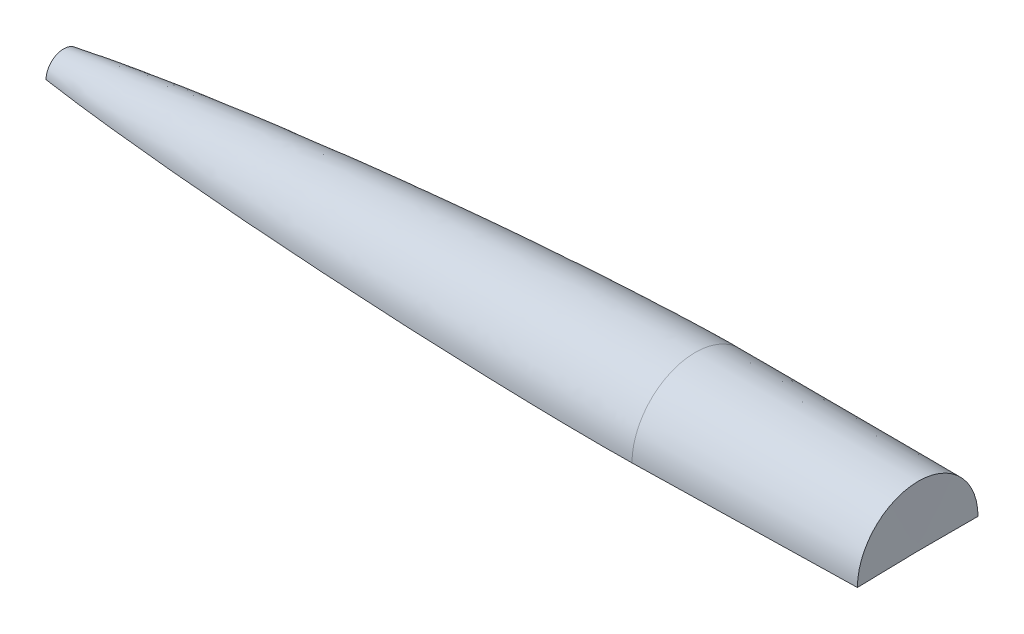
SolidWorks part; units mm, degrees
ref_plane "Front" through (0, 0, 0) normal (0, 0, 1) x (1, 0, 0)
ref_plane "Top" through (0, 0, 0) normal (0, 1, 0) x (1, 0, 0)
ref_plane "Right" through (0, 0, 0) normal (1, 0, 0) x (0, 0, -1)
other "von Karman body"
sketch "Sketch1" plane through (0, 0, 0) normal (0, 1, 0) x (1, 0, 0)
  line L0 (851.3046, 76.2) -> (1122.3515, 76.2)
  line L1 (1122.3515, 1.3141) -> (1122.3515, 76.2)
  line L2 (1122.3515, 1.3141) -> (88.7676, -9.9008)
  line L3 (88.7676, -9.9008) -> (85.0478, 11.756)
  spline S2 degree 4 poles (12.9881, -5.0079) (13.0153, -4.9845) (13.0706, -4.939) (13.1856, -4.8536) (13.4201, -4.7006) (13.7506, -4.5125) (14.2316, -4.2679) (14.9316, -3.9472) (15.975, -3.5139) (17.6957, -2.8712) (20.7062, -1.8693) (26.0797, -0.2977) (33.3966, 1.566) (41.1326, 3.3372) (48.5891, 4.9242) (54.2713, 6.0794) (58.4117, 6.8975) (62.2634, 7.6406) (65.7215, 8.2958) (69.3044, 8.9605) (72.6782, 9.578) (76.4079, 10.2463) (79.548, 10.8035) (83.6569, 11.5178) (86.3774, 11.985) (90.4166, 12.6708) (93.5371, 13.1913) (97.1703, 13.7927) (100.5058, 14.3362) (104.0171, 14.9033) (107.4312, 15.4474) (111.7605, 16.1307) (116.9253, 16.9339) (122.9723, 17.8587) (129.8755, 18.8939) (138.5137, 20.1657) (148.8818, 21.6563) (160.9862, 23.3488) (174.8269, 25.2247) (192.1371, 27.503) (212.9219, 30.1385) (237.1871, 33.0845) (264.9371, 36.2943) (292.7033, 39.3616) (320.4837, 42.2972) (348.2768, 45.1099) (376.0815, 47.806) (403.8967, 50.3908) (431.7217, 52.8678) (459.5558, 55.2399) (487.3986, 57.5088) (515.2495, 59.6754) (543.1081, 61.7397) (577.9407, 64.1913) (612.7853, 66.4682) (647.6414, 68.5635) (689.4819, 70.8435) (724.3599, 72.5349) (759.2486, 73.9926) (792.5651, 75.1094) (814.625, 75.6938) (832.4055, 76.0379) (843.2047, 76.166) (848.6046, 76.2013) (851.3046, 76.2) knots 0 0 0 0 0 0.00017 0.000339 0.000679 0.001327 0.001972 0.002897 0.004328 0.006683 0.010678 0.017939 0.030863 0.042482 0.048291 0.0541 0.058325 0.06255 0.066775 0.071 0.075225 0.07945 0.083675 0.0879 0.092039 0.096178 0.100317 0.104456 0.108595 0.112734 0.116873 0.121012 0.129289 0.137567 0.145845 0.154123 0.170679 0.187234 0.20379 0.220346 0.253457 0.286568 0.31968 0.352791 0.385902 0.419014 0.452125 0.485236 0.518348 0.551459 0.58457 0.617682 0.650793 0.683905 0.750127 0.783239 0.81635 0.882573 0.915684 0.948795 0.974398 0.987199 1 1 1 1 1 construction
  spline S3 degree 4 poles (85.0478, 11.756) (85.8326, 11.8908) (87.4028, 12.1591) (90.4166, 12.6708) (93.5371, 13.1913) (97.1703, 13.7927) (100.5058, 14.3362) (104.0171, 14.9033) (107.4312, 15.4474) (111.7605, 16.1307) (116.9253, 16.9339) (122.9723, 17.8587) (129.8755, 18.8939) (138.5137, 20.1657) (148.8818, 21.6563) (160.9862, 23.3488) (174.8269, 25.2247) (192.1371, 27.503) (212.9219, 30.1385) (237.1871, 33.0845) (264.9371, 36.2943) (292.7033, 39.3616) (320.4837, 42.2972) (348.2768, 45.1099) (376.0815, 47.806) (403.8967, 50.3908) (431.7217, 52.8678) (459.5558, 55.2399) (487.3986, 57.5088) (515.2495, 59.6754) (543.1081, 61.7397) (577.9407, 64.1913) (612.7853, 66.4682) (647.6414, 68.5635) (689.4819, 70.8435) (724.3599, 72.5349) (759.2486, 73.9926) (792.5651, 75.1094) (814.625, 75.6938) (832.4055, 76.0379) (843.2047, 76.166) (848.6046, 76.2013) (851.3046, 76.2) knots 0.0879 0.0879 0.0879 0.0879 0.0879 0.092039 0.096178 0.100317 0.104456 0.108595 0.112734 0.116873 0.121012 0.129289 0.137567 0.145845 0.154123 0.170679 0.187234 0.20379 0.220346 0.253457 0.286568 0.31968 0.352791 0.385902 0.419014 0.452125 0.485236 0.518348 0.551459 0.58457 0.617682 0.650793 0.683905 0.750127 0.783239 0.81635 0.882573 0.915684 0.948795 0.974398 0.987199 1 1 1 1 1
  point P5 (0, 0)
  dimension "D1" = 1033.5838
revolve "main body" add sketch "Sketch1" angle 180 about L2
scale "Scale1" [suppressed]
sketch "Sketch4" plane through (0, 0, 0) normal (1, 0, 0) x (0, 0, -1)
  circle A0 centre (-9.9008, 0) radius 7.4889
extrude "Cut-Extrude3" cut sketch "Sketch4" along normal blind 314.706
